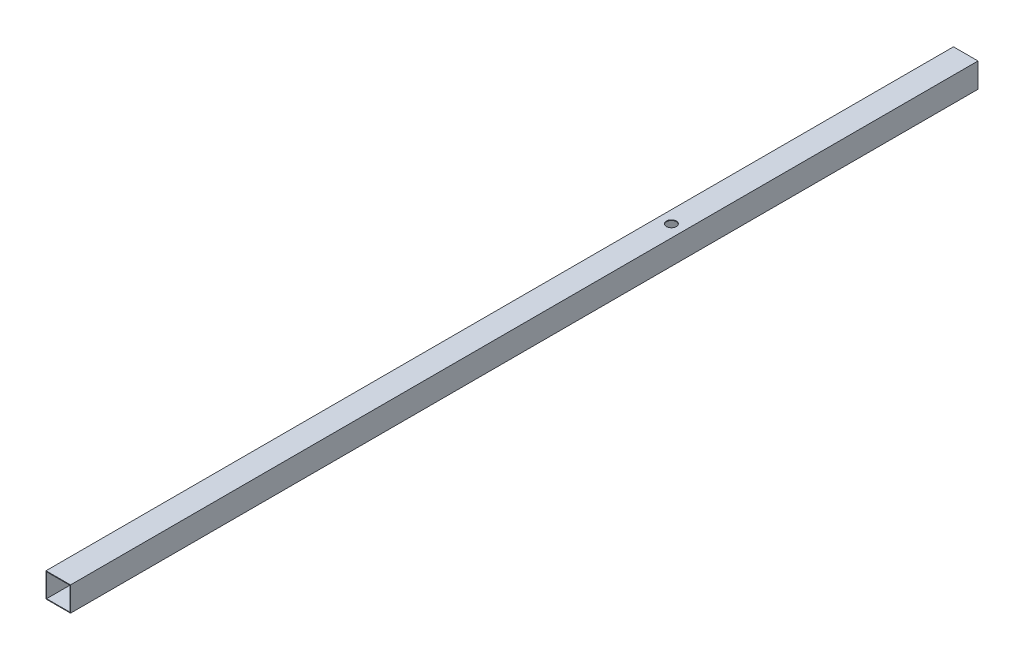
SolidWorks part; units mm, degrees
ref_plane "Front Plane" through (0, 0, 0) normal (0, 0, 1) x (1, 0, 0)
ref_plane "Top Plane" through (0, 0, 0) normal (0, 1, 0) x (1, 0, 0)
ref_plane "Right Plane" through (0, 0, 0) normal (1, 0, 0) x (0, 0, -1)
sketch "Sketch2" plane through (0, 0, 0) normal (0, 0, 1) x (1, 0, 0)
  line L1 (-10, 10) -> (10, 10)
  line L2 (-10, 10) -> (-10, -10)
  line L3 (-10, -10) -> (10, -10)
  line L4 (10, 10) -> (10, -10)
  line L5 (-10, 10) -> (10, -10) construction
  line L6 (-10, -10) -> (10, 10) construction
  point P0 (0, 0)
  dimension "D1" = 20
  dimension "D2" = 20
extrude "Boss-Extrude1" add sketch "Sketch2" along normal blind 740
sketch "Sketch3" plane through (0, 0, 0) normal (0, 0, -1) x (-1, 0, 0)
  line L1 (-9.5, 9.5) -> (9.5, 9.5)
  line L2 (-9.5, 9.5) -> (-9.5, -9.5)
  line L3 (-9.5, -9.5) -> (9.5, -9.5)
  line L4 (9.5, 9.5) -> (9.5, -9.5)
  line L5 (-9.5, 9.5) -> (9.5, -9.5) construction
  line L6 (-9.5, -9.5) -> (9.5, 9.5) construction
  point P0 (0, 0)
  dimension "D1" = 19
  dimension "D2" = 19
extrude "Cut-Extrude1" cut sketch "Sketch3" against normal blind 740
sketch "Sketch5" plane through (0, -10, 0) normal (0, -1, 0) x (1, 0, 0)
  line L0 (0, 740) -> (0, 0) construction
  line L1 (-10, 740) -> (10, 740) construction
  circle A0 centre (0, 240) radius 4
  dimension "D1" = 8
  dimension "D2" = 500
extrude "Cut-Extrude2" cut sketch "Sketch5" against normal blind 20
